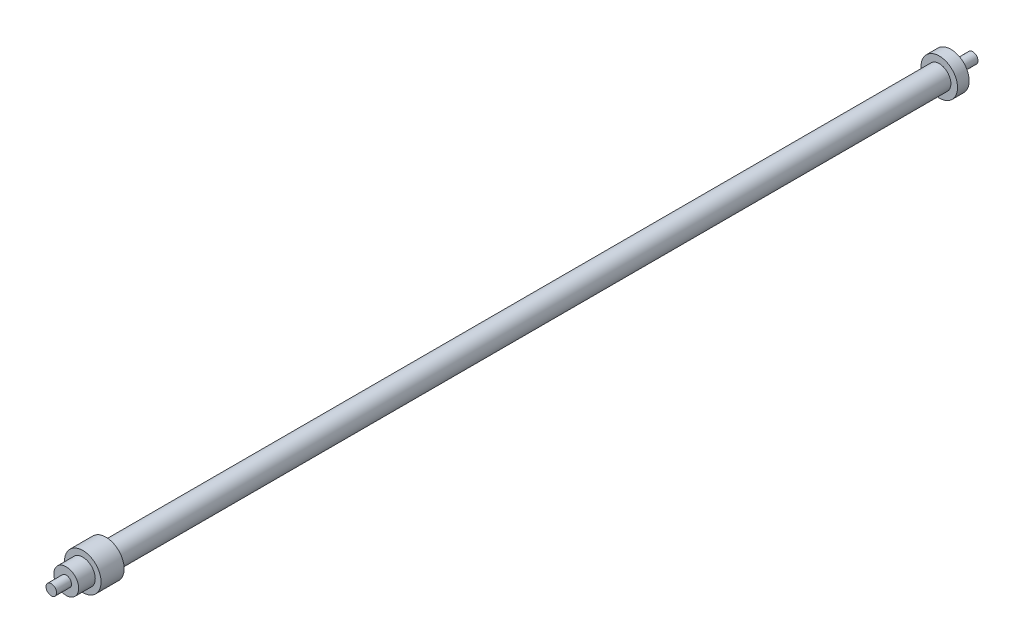
SolidWorks part; units mm, degrees
ref_plane "Front Plane" through (0, 0, 0) normal (0, 0, 1) x (1, 0, 0)
ref_plane "Top Plane" through (0, 0, 0) normal (0, 1, 0) x (1, 0, 0)
ref_plane "Right Plane" through (0, 0, 0) normal (1, 0, 0) x (0, 0, -1)
sketch "Sketch6" plane through (0, 0, 0) normal (1, 0, 0) x (0, 0, -1)
  line L0 (-139.8651, 32.5) -> (415.1349, 32.5)
  line L2 (-139.8651, 35.675) -> (-139.8651, 32.5)
  line L3 (-139.8651, 35.675) -> (-130.8651, 35.675)
  line L4 (-130.8651, 35.675) -> (-130.8651, 40)
  line L5 (-130.8651, 40) -> (-120.8651, 40)
  line L6 (-120.8651, 40) -> (-120.8651, 43.5)
  line L7 (-120.8651, 43.5) -> (-106.9551, 43.5)
  line L8 (-106.9551, 43.5) -> (-106.9551, 39.5)
  line L9 (-106.9551, 39.5) -> (394.9849, 39.5)
  line L10 (394.9849, 39.5) -> (394.9849, 43.5)
  line L11 (394.9849, 43.5) -> (401.9849, 43.5)
  line L12 (401.9849, 43.5) -> (401.9849, 36.5)
  line L13 (401.9849, 36.5) -> (405.0349, 36.5)
  line L14 (405.0349, 36.5) -> (405.0349, 35.675)
  line L15 (405.0349, 35.675) -> (415.1349, 35.675)
  line L16 (415.1349, 35.675) -> (415.1349, 32.5)
  line L17 (405.0349, 29.325) -> (415.1349, 29.325) construction
  line L18 (405.0349, 28.5) -> (405.0349, 29.325) construction
  line L19 (401.9849, 28.5) -> (405.0349, 28.5) construction
  line L20 (401.9849, 21.5) -> (401.9849, 28.5) construction
  line L21 (394.9849, 21.5) -> (401.9849, 21.5) construction
  line L22 (394.9849, 25.5) -> (394.9849, 21.5) construction
  line L23 (-106.9551, 25.5) -> (394.9849, 25.5) construction
  line L24 (-106.9551, 21.5) -> (-106.9551, 25.5) construction
  line L25 (-120.8651, 21.5) -> (-106.9551, 21.5) construction
  line L26 (-120.8651, 25) -> (-120.8651, 21.5) construction
  line L27 (-130.8651, 25) -> (-120.8651, 25) construction
  line L28 (-130.8651, 29.325) -> (-130.8651, 25) construction
  line L29 (-139.8651, 29.325) -> (-130.8651, 29.325) construction
  line L30 (-120.8651, 43.5) -> (-120.8651, 21.5) construction
  line L31 (394.9849, 43.5) -> (394.9849, 21.5) construction
  line L32 (-139.8651, 35.675) -> (-139.8651, 29.325) construction
  line L33 (415.1349, 35.675) -> (415.1349, 29.325) construction
  dimension "D1" = 555
  dimension "D2" = 6.35
  dimension "D3" = 15
  dimension "D4" = 22
  dimension "D5" = 14
  dimension "D6" = 9
  dimension "D7" = 19
  dimension "D8" = 13.91
  dimension "D9" = 7
  dimension "D10" = 10.1
  dimension "D11" = 13.15
  dimension "D12" = 8
revolve "Revolve1" add sketch "Sketch6" angle 360 about L0
